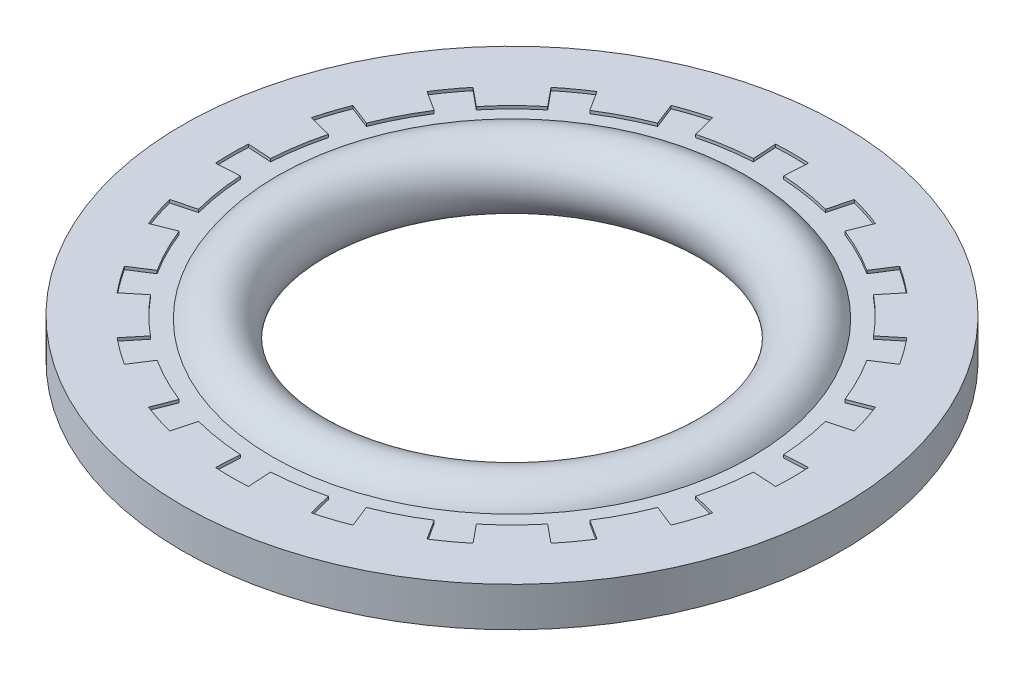
SolidWorks part; units mm, degrees
ref_plane "Front Plane" through (0, 0, 0) normal (0, 0, 1) x (1, 0, 0)
ref_plane "Top Plane" through (0, 0, 0) normal (0, 1, 0) x (1, 0, 0)
ref_plane "Right Plane" through (0, 0, 0) normal (1, 0, 0) x (0, 0, -1)
sketch "Sketch1" plane through (0, 0, 0) normal (0, 0, 1) x (1, 0, 0)
  line L0 (-8.509, 0) -> (8.509, 0) construction
  line L1 (0, 0) -> (0, 0.508) construction
  line L3 (-8.509, 0.508) -> (-5.4356, 0.508)
  line L4 (-8.509, 0.508) -> (-8.509, -0.508)
  line L5 (-8.509, -0.508) -> (-5.4356, -0.508)
  line L6 (-5.4356, 0.508) -> (-5.4356, -0.508)
  circle A0 centre (-5.4356, 0) radius 0.8636
  point P3 (-4.572, 0)
  dimension "D1" = 1.7272
  dimension "D2" = 12.5984
  dimension "ID" = 9.144
  dimension "thickness" = 1.016
  dimension "OD" = 17.018
sketch "Sketch2" plane through (0, 0, 0) normal (0, 0, 1) x (1, 0, 0)
  line L0 (-8.509, 0.508) -> (-8.509, -0.508) construction
  line L2 (-8.509, 0.508) -> (-5.4356, 0.508) construction
  line L3 (-8.509, -0.508) -> (-5.4356, -0.508) construction
  line L4 (-8.509, 0.508) -> (-8.509, -0.508)
  line L5 (-6.6331, 0.508) -> (-6.6331, -0.508)
  line L6 (-8.509, 0.508) -> (-6.6331, 0.508)
  line L7 (-8.509, -0.508) -> (-6.6331, -0.508)
  line L8 (0, 0) -> (0, 0.508) construction
  line L9 (0, 0) -> (0, 0.508) construction
  line L10 (-6.2992, 0.508) -> (-6.2992, -0.508) construction
  circle A0 centre (-5.4356, 0) radius 0.8636 construction
  dimension "D1" = 13.2661
revolve "Revolve1" add sketch "Sketch2" angle 360 about L9
sketch "Sketch3" plane through (0, 0.508, 0) normal (0, 1, 0) x (1, 0, 0)
  line L0 (-0.3896, 6.6216) -> (-0.4254, 7.2316)
  line L1 (0.3896, 6.6216) -> (0.4254, 7.2316)
  circle A0 centre (0, 0) radius 7.2441 construction
  circle A1 centre (0, 0) radius 6.6331 construction
  arc A3 (0.4254, 7.2316) -> (-0.4254, 7.2316) centre (0, 0) ccw
  arc A4 (0.3896, 6.6216) -> (-0.3896, 6.6216) centre (0, 0) ccw
  dimension "D1" = 14.4882
  dimension "D2" = 0.8509
extrude "Cut-Extrude1" cut sketch "Sketch3" against normal through all
pattern_circular "CirPattern1" count 20 over 360 about axis through (0, 0, 0) along (0, 1, 0) of "Cut-Extrude1"
sketch "Sketch4" plane through (0, 0, 0) normal (0, 0, 1) x (1, 0, 0)
  line L3 (-7.2441, -0.4318) -> (-6.1835, -0.4318)
  line L4 (-7.2441, 0.4318) -> (-6.1835, 0.4318)
  line L5 (-7.2441, 0.4318) -> (-7.2441, -0.4318)
  line L6 (0, 0) -> (0, 0.508) construction
  line L7 (0, 0) -> (0, 0.508) construction
  circle A0 centre (-5.4356, 0) radius 0.8636 construction
  arc A1 (-6.1835, -0.4318) -> (-6.1835, 0.4318) centre (-5.4356, 0) ccw
  dimension "D1" = 0.8636
  dimension "D2" = 14.4882
revolve "Revolve2" add sketch "Sketch4" angle 360 about L7
sketch "Sketch5" plane through (0, 0, 0) normal (0, 1, 0) x (1, 0, 0)
  circle A0 centre (0, 0) radius 4.572
  circle A1 centre (0, 0) radius 8.509 construction
  circle A2 centre (0, 0) radius 8.509
equation "\"D1@Sketch1\" = \"thickness@Sketch1\"*1.7"
equation "\"D2@Sketch3\" = \"OD@Sketch1\"/20"
equation "\"D1@Sketch4\" = \"thickness@Sketch1\"*.85"
equation "\"D1@Sketch3\" = \"D2@Sketch1\"*1.15"
equation "\"D1@Sketch2\" = \"D2@Sketch1\"*1.053"
equation "\"D2@Sketch4\" = \"D1@Sketch3\""
